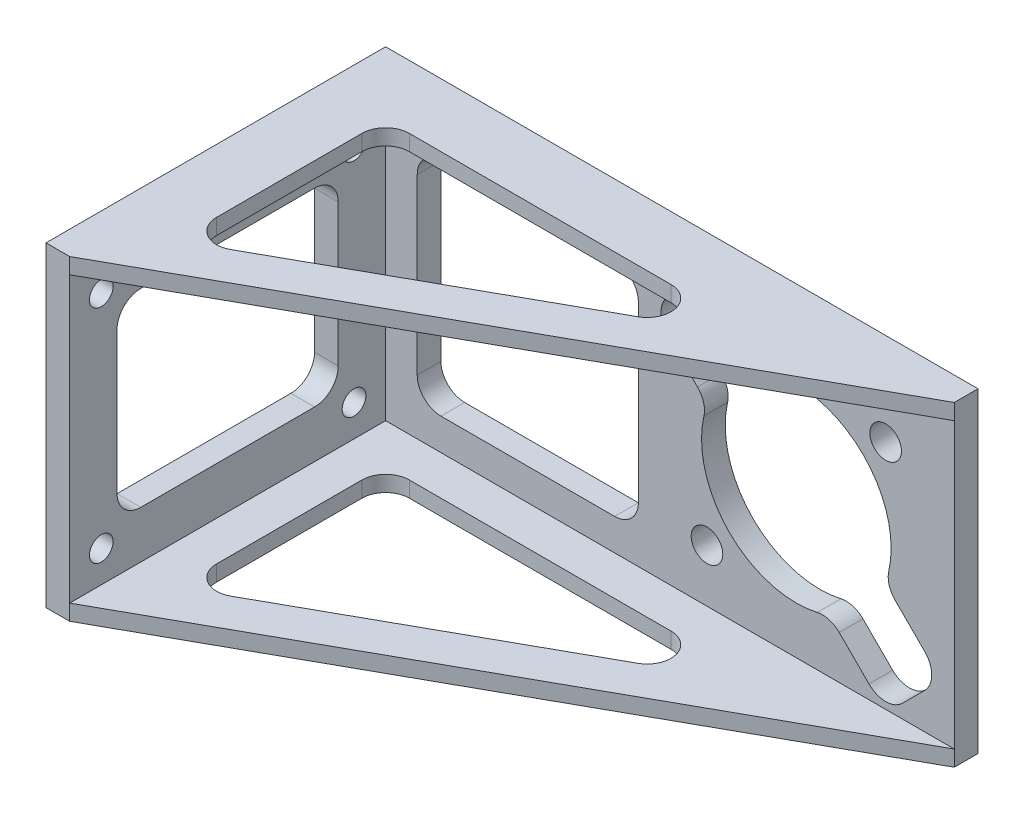
SolidWorks part; units mm, degrees
material "6061 合金"
ref_plane "前视基准面" through (0, 0, 0) normal (0, 0, 1) x (1, 0, 0)
ref_plane "上视基准面" through (0, 0, 0) normal (0, 1, 0) x (1, 0, 0)
ref_plane "右视基准面" through (0, 0, 0) normal (1, 0, 0) x (0, 0, -1)
sketch "草图1" plane through (0, 0, 0) normal (0, 0, 1) x (1, 0, 0)
  line L0 (0, 0) -> (11.3137, 11.3137) construction
  line L2 (-20, -20) -> (20, -20)
  line L3 (-20, -20) -> (-20, 20)
  line L4 (-20, 20) -> (20, 20)
  line L5 (20, -20) -> (20, 20)
  line L6 (-20, -20) -> (20, 20) construction
  line L7 (-20, 20) -> (20, -20) construction
  circle A0 centre (0, 0) radius 16 construction
  circle A1 centre (11.3137, 11.3137) radius 2
  circle A2 centre (11.3137, -11.3137) radius 2
  circle A3 centre (-11.3137, -11.3137) radius 2
  circle A4 centre (-11.3137, 11.3137) radius 2
  circle A5 centre (0, 0) radius 12
  point P14 (0, 0)
  dimension "D1" = 32
  dimension "D2" = 4
  dimension "D5" = 24
  dimension "D4" = 40
  dimension "D3" = 4
extrude "凸台-拉伸1" add sketch "草图1" along normal blind 3
sketch "草图2" plane through (0, 0, 3) normal (0, 0, 1) x (1, 0, 0)
  line L0 (0, 0) -> (-55, 0) construction
  line L2 (-20, 20) -> (-55, 20)
  line L3 (-20, 20) -> (-20, -20)
  line L4 (-20, -20) -> (-55, -20)
  line L5 (-55, 20) -> (-55, -20)
  dimension "D1" = 55
  dimension "D2" = 40
  dimension "D3" = 35
extrude "凸台-拉伸2" add sketch "草图2" against normal blind 3
sketch "草图3" plane through (0, 0, 3) normal (0, 0, 1) x (1, 0, 0)
  line L1 (-55, 20) -> (-52, 20)
  line L2 (-55, 20) -> (-55, -20)
  line L3 (-55, -20) -> (-52, -20)
  line L4 (-52, 20) -> (-52, -20)
  line L5 (-55, -20) -> (20, -20) construction
  dimension "D1" = 40
  dimension "D2" = 3
extrude "凸台-拉伸3" add sketch "草图3" along normal blind 40
sketch "草图4" plane through (0, 20, 0) normal (0, 1, 0) x (1, 0, 0)
  line L0 (-52, -43) -> (20, -3)
  line L5 (20, -3) -> (20, 0)
  line L6 (-52, -43) -> (-52, -3)
  line L7 (-52, -3) -> (20, -3)
  line M9 (-52, -43) -> (-52, -3)
  line M10 (-52, -3) -> (20, -3)
extrude "凸台-拉伸4" add sketch "草图4" against normal blind 2 contours L0 M9 M10
sketch "草图5" plane through (0, -20, 0) normal (0, -1, 0) x (1, 0, 0)
  line L0 (-52, 43) -> (-52, 3)
  line L1 (-52, 3) -> (20, 3)
  line L2 (20, 3) -> (-52, 43)
extrude "凸台-拉伸5" add sketch "草图5" against normal blind 2
sketch "草图6" plane through (-52, 0, 0) normal (1, 0, 0) x (0, 0, -1)
  line L0 (-43, 0) -> (-3, 0) construction
  line L1 (-43, -18) -> (-43, 18) construction
  line L2 (-3, -18) -> (-3, 18) construction
  line L3 (-37, 12) -> (-9, 12)
  line L4 (-39, -14) -> (-7, -14) construction
  line L5 (-39, -14) -> (-39, 14) construction
  line L6 (-39, 14) -> (-7, 14) construction
  line L7 (-7, -14) -> (-7, 14) construction
  line L8 (-39, -14) -> (-7, 14) construction
  line L9 (-39, 14) -> (-7, -14) construction
  line L10 (-9, -12) -> (-9, 12)
  line L11 (-37, -12) -> (-9, -12)
  line L12 (-37, -12) -> (-37, 12)
  circle A0 centre (-39, 14) radius 1.5
  circle A1 centre (-7, 14) radius 1.5
  circle A2 centre (-7, -14) radius 1.5
  circle A3 centre (-39, -14) radius 1.5
  point P6 (-23, 0)
  dimension "D3" = 3
  dimension "D4" = 3
  dimension "D5" = 3
  dimension "D6" = 3
  dimension "D1" = 28
  dimension "D2" = 32
  dimension "D7" = 2
extrude "切除-拉伸1" cut sketch "草图6" against normal blind 12
fillet "圆角1" radius 3 4 edges at (-53.5, -12, 9) (-53.5, -12, 37) (-53.5, 12, 37) (-53.5, 12, 9)
sketch "草图7" plane through (0, 0, 3) normal (0, 0, 1) x (1, 0, 0)
  line L0 (-52, 0) -> (-48, 0) construction
  line L1 (-52, -18) -> (-52, 18) construction
  line L3 (-48, -14) -> (-20, -14)
  line L4 (-48, -14) -> (-48, 14)
  line L5 (-48, 14) -> (-20, 14)
  line L6 (-20, -14) -> (-20, 14)
  line L7 (-48, -14) -> (-20, 14) construction
  line L8 (-48, 14) -> (-20, -14) construction
  point P7 (-34, 0)
  dimension "D1" = 28
  dimension "D2" = 18
extrude "切除-拉伸2" cut sketch "草图7" against normal blind 12
fillet "圆角2" radius 3 4 edges at (-20, -14, 1.5) (-48, -14, 1.5) (-48, 14, 1.5) (-20, 14, 1.5)
sketch "草图8" plane through (0, 20, 0) normal (0, 1, 0) x (1, 0, 0)
  line L0 (-52, -43) -> (-52, -3) construction
  line L1 (-52, -3) -> (20, -3) construction
  line L2 (20, -3) -> (-52, -43) construction
  line L3 (-47, -34.5024) -> (-47, -8)
  line L4 (-47, -8) -> (0.7044, -8)
  line L5 (0.7044, -8) -> (-47, -34.5024)
  dimension "D1" = 40
  dimension "D2" = 5
extrude "切除-拉伸3" cut sketch "草图8" against normal blind 49
fillet "圆角3" radius 3 3 edges at (-47, 19, 8) (-47, 19, 34.5024) (0.7044, 19, 8)
fillet "圆角4" radius 3 3 edges at (-47, -19, 34.5024) (-47, -19, 8) (0.7044, -19, 8)
sketch "草图9" plane through (0, 0, 3) normal (0, 0, 1) x (1, 0, 0)
  line L20 (-4.9497, 12.0208) -> (-1.9985, 9.0695)
  line L21 (-1.9985, 9.0695) -> (12.0208, -4.9497)
  line L22 (12.0208, -4.9497) -> (16.2635, -9.1924)
  line L23 (16.2635, -13.435) -> (13.435, -16.2635)
  line L24 (9.1924, -16.2635) -> (4.9497, -12.0208)
  line L25 (-9.0695, 1.9985) -> (4.9497, -12.0208)
  line L26 (-12.0208, 4.9497) -> (-9.0695, 1.9985)
  line L27 (-12.0208, 4.9497) -> (-16.2635, 9.1924)
  line L28 (-16.2635, 13.435) -> (-13.435, 16.2635)
  line L29 (-9.1924, 16.2635) -> (-4.9497, 12.0208)
  arc A8 (16.2635, -13.435) -> (16.2635, -9.1924) centre (14.1421, -11.3137) ccw
  arc A9 (9.1924, -16.2635) -> (13.435, -16.2635) centre (11.3137, -14.1421) ccw
  arc A10 (-16.2635, 13.435) -> (-16.2635, 9.1924) centre (-14.1421, 11.3137) ccw
  arc A11 (-9.1924, 16.2635) -> (-13.435, 16.2635) centre (-11.3137, 14.1421) ccw
extrude "切除-拉伸4" cut sketch "草图9" against normal blind 10
fillet "圆角5" radius 3 4 edges at (11.2492, -4.1781, 1.5) (-4.1781, 11.2492, 1.5) (-11.2492, 4.1781, 1.5) (4.1781, -11.2492, 1.5)
